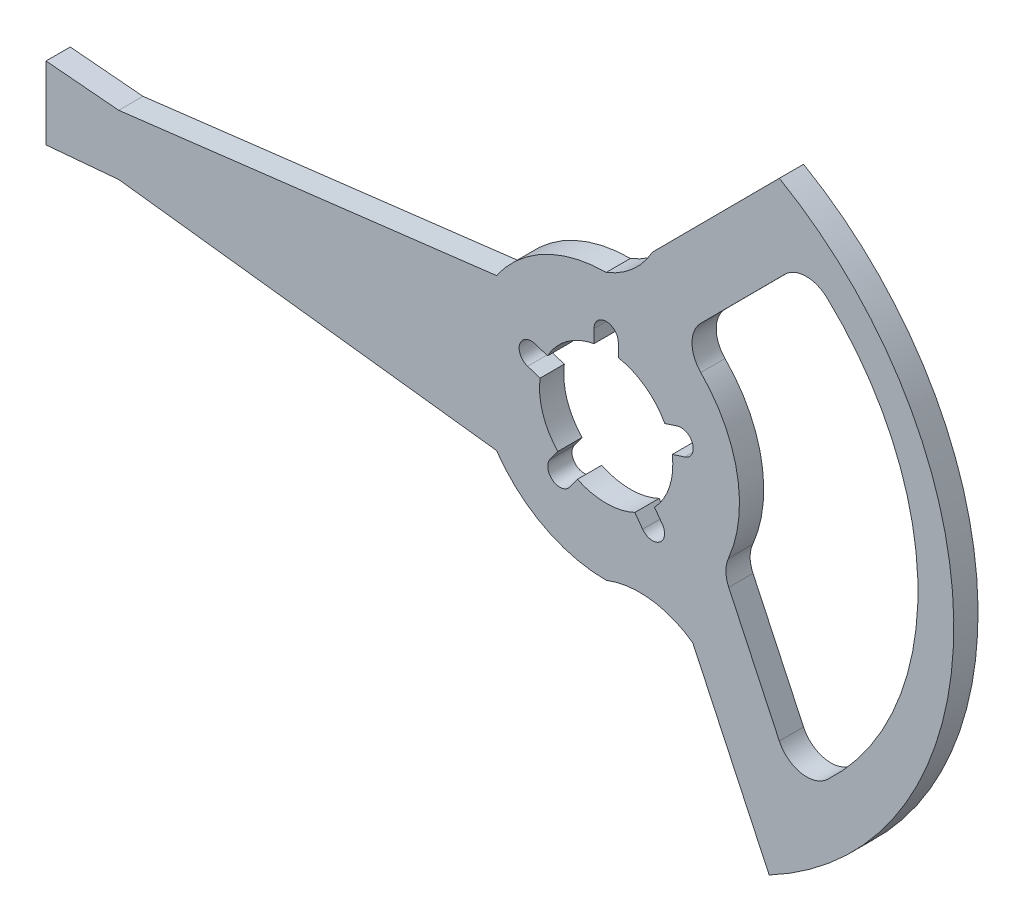
SolidWorks part; units mm, degrees
material "Plain Carbon Steel"
ref_plane "Front Plane" through (0, 0, 0) normal (0, 0, 1) x (1, 0, 0)
ref_plane "Top Plane" through (0, 0, 0) normal (0, 1, 0) x (1, 0, 0)
ref_plane "Right Plane" through (0, 0, 0) normal (1, 0, 0) x (0, 0, -1)
sketch "Sketch1" plane through (0, 0, 0) normal (0, 0, 1) x (1, 0, 0)
  line L0 (-1.9999, 12.9858) -> (-1.9999, 10.8167)
  line L2 (1.9999, 12.9858) -> (1.9999, 10.8167)
  line L7 (11.7322, 5.9149) -> (9.6692, 5.2446)
  line L8 (12.9682, 2.1108) -> (10.9053, 1.4405)
  line L9 (9.2508, -9.3302) -> (7.9759, -7.5753)
  line L10 (6.0148, -11.6812) -> (4.7399, -9.9264)
  line L11 (-6.0148, -11.6812) -> (-4.7399, -9.9264)
  line L12 (-9.2508, -9.3302) -> (-7.9759, -7.5753)
  line L13 (-12.9682, 2.1108) -> (-10.9053, 1.4405)
  line L14 (-11.7322, 5.9149) -> (-9.6692, 5.2446)
  line L15 (7.6246, 28.7056) -> (28.5769, 49.7461)
  line L16 (-18.1039, 12.5) -> (-80.44, 4.9501)
  line L17 (-18.1039, -12.5) -> (-80.44, -4.9501)
  line L18 (-80.44, -4.9501) -> (-92.44, -6)
  line L19 (-92.44, -6) -> (-92.44, 6)
  line L20 (-92.44, 6) -> (-80.44, 4.9501)
  line L21 (-92.44, 6) -> (-71.7717, 6) construction
  line L22 (-92.44, -6) -> (-71.7717, -6) construction
  line L23 (14.2934, -23.7881) -> (26.8989, -50.6731)
  line L24 (15.6209, 22.5477) -> (29.4798, 36.4649)
  line L25 (20.2307, -12.8953) -> (28.5686, -30.6783)
  line L26 (-92.44, 0) -> (57.37, 0) construction
  arc A0 (20.173, -8.7778) -> (15.615, 15.4975) centre (0, 0) ccw
  arc A2 (-1.9999, 12.9858) -> (1.9999, 12.9858) centre (0, 13) cw
  arc A3 (11.7322, 5.9149) -> (12.9682, 2.1108) centre (12.3637, 4.0172) cw
  arc A4 (9.2508, -9.3302) -> (6.0148, -11.6812) centre (7.6412, -10.5172) cw
  arc A5 (-6.0148, -11.6812) -> (-9.2508, -9.3302) centre (-7.6412, -10.5172) cw
  arc A6 (-12.9682, 2.1108) -> (-11.7322, 5.9149) centre (-12.3637, 4.0172) cw
  arc A7 (-1.9999, 10.8167) -> (-9.6692, 5.2446) centre (0, 0) ccw
  arc A8 (9.6692, 5.2446) -> (1.9999, 10.8167) centre (0, 0) ccw
  arc A9 (7.9759, -7.5753) -> (10.9053, 1.4405) centre (0, 0) ccw
  arc A10 (-4.7399, -9.9264) -> (4.7399, -9.9264) centre (0, 0) ccw
  arc A11 (-10.9053, 1.4405) -> (-7.9759, -7.5753) centre (0, 0) ccw
  arc A13 (0, 22) -> (7.6246, 28.7056) centre (-5.5091, 35.9517) ccw
  arc A14 (0, -22) -> (14.2934, -23.7881) centre (5.5134, -35.95) cw
  arc A15 (26.8989, -50.6731) -> (28.5769, 49.7461) centre (0, 0) ccw
  arc A16 (36.4224, 36.6031) -> (36.5041, -32.214) centre (4.4811, 2.1566) cw
  arc A17 (28.5686, -30.6783) -> (36.5041, -32.214) centre (33.0957, -28.5557) ccw
  arc A18 (29.4798, 36.4649) -> (36.4224, 36.6031) centre (33.0227, 32.9368) cw
  arc A19 (0, 22) -> (0, -22) centre (0, 0) ccw
  arc A20 (20.173, -8.7778) -> (20.2307, -12.8953) centre (24.7578, -10.7727) ccw
  arc A21 (15.615, 15.4975) -> (15.6209, 22.5477) centre (19.1639, 19.0196) cw
  point P10 (0, 15)
  point P35 (0, 0)
  point P46 (-92.44, 0)
  point P55 (0, 0)
  point P59 (32.7083, 39.7071)
  point P63 (-12.9832, 2.1566)
  point P64 (-11.7322, 5.9149)
  point P65 (-1.9999, 13)
  dimension "D2" = 44
  dimension "D3" = 2
  dimension "D13" = 10
  dimension "D17" = 46.9767
  dimension "D19" = 22
  dimension "D20" = 57.37
  dimension "D21" = 5
  dimension "D4" = 5
  dimension "D6" = 1.9999
  dimension "D5" = 13
  dimension "D7" = 110
  dimension "D8" = 15
  dimension "D22" = 19.1639
  dimension "D24" = 35.9517
  dimension "D27" = 33.0227
  dimension "D18" = 5
  dimension "D9" = 12
  dimension "D10" = 12
  dimension "D11" = 92.44
  dimension "D12" = 25
  dimension "D14" = 5
  dimension "D15" = 12
  dimension "D16" = 5
  dimension "D23" = 29.6935
  dimension "D25" = 35.95
  dimension "D26" = 14.8525
extrude "Boss-Extrude2" add sketch "Sketch1" along normal blind 4 contours A19 L16 L20 L19 L18 L17 | A13 A19 A14 L23 A15 L15 A11 L13 A6 L14 A7 L0 A2 L2 A8 L7 A3 L8 A9 L9 A4 L10 A10 L11 A5 L12 A0 A21 L24 A18 A16 A17 L25 A20
